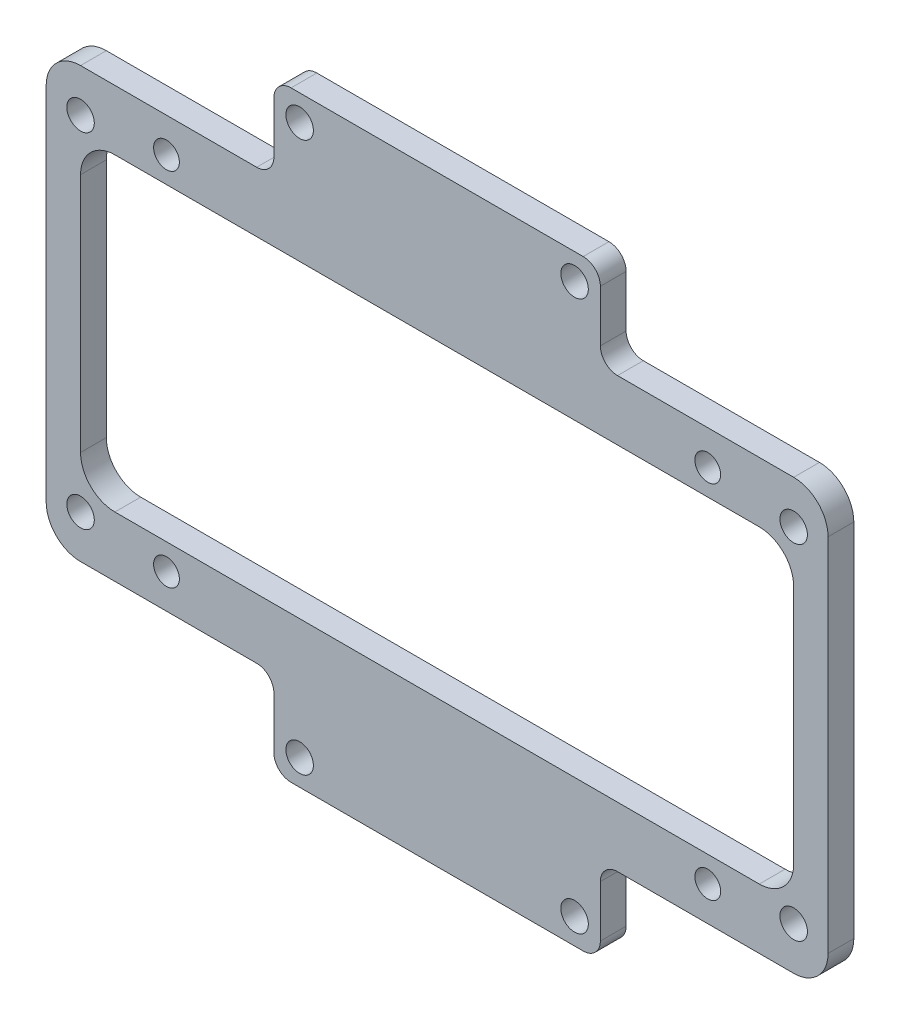
SolidWorks part; units mm, degrees
material "A-玻璃纤维"
ref_plane "前视基准面" through (0, 0, 0) normal (0, 0, 1) x (1, 0, 0)
ref_plane "上视基准面" through (0, 0, 0) normal (0, 1, 0) x (1, 0, 0)
ref_plane "右视基准面" through (0, 0, 0) normal (1, 0, 0) x (0, 0, -1)
sketch "草图1" plane through (0, 0, 0) normal (0, 0, 1) x (1, 0, 0)
  line L1 (-45.5, -25) -> (45.5, -25)
  line L2 (-45.5, -25) -> (-45.5, 25)
  line L3 (-45.5, 25) -> (45.5, 25)
  line L4 (45.5, -25) -> (45.5, 25)
  line L5 (-45.5, -25) -> (45.5, 25) construction
  line L6 (-45.5, 25) -> (45.5, -25) construction
  line L7 (-41.5, -18) -> (41.5, -18)
  line L8 (-41.5, -18) -> (-41.5, 18)
  line L9 (-41.5, 18) -> (41.5, 18)
  line L10 (41.5, -18) -> (41.5, 18)
  line L11 (-41.5, -18) -> (41.5, 18) construction
  line L12 (-41.5, 18) -> (41.5, -18) construction
  point P0 (0, 0)
  point P6 (0, 0)
  dimension "D1" = 50
  dimension "D2" = 91
  dimension "D3" = 36
  dimension "D4" = 83
extrude "凸台-拉伸1" add sketch "草图1" along normal blind 3
sketch "草图2" plane through (0, 0, 3) normal (0, 0, 1) x (1, 0, 0)
  line L1 (-31.5, -21) -> (31.5, -21) construction
  line L2 (-31.5, -21) -> (-31.5, 21) construction
  line L3 (-31.5, 21) -> (31.5, 21) construction
  line L4 (31.5, -21) -> (31.5, 21) construction
  line L5 (-31.5, -21) -> (31.5, 21) construction
  line L6 (-31.5, 21) -> (31.5, -21) construction
  circle A0 centre (31.5, 21) radius 1.5
  circle A1 centre (31.5, -21) radius 1.5
  circle A2 centre (-31.5, -21) radius 1.5
  circle A3 centre (-31.5, 21) radius 1.5
  point P0 (0, 0)
  dimension "D3" = 3
  dimension "D1" = 42
  dimension "D2" = 63
extrude "切除-拉伸1" cut sketch "草图2" against normal blind 3
sketch "草图3" plane through (0, 0, 3) normal (0, 0, 1) x (1, 0, 0)
  line L1 (-41.5, -20) -> (41.5, -20) construction
  line L2 (-41.5, -20) -> (-41.5, 20) construction
  line L3 (-41.5, 20) -> (41.5, 20) construction
  line L4 (41.5, -20) -> (41.5, 20) construction
  line L5 (-41.5, -20) -> (41.5, 20) construction
  line L6 (-41.5, 20) -> (41.5, -20) construction
  circle A0 centre (41.5, 20) radius 1.6
  circle A1 centre (41.5, -20) radius 1.6
  circle A2 centre (-41.5, -20) radius 1.6
  circle A3 centre (-41.5, 20) radius 1.6
  point P0 (0, 0)
  dimension "D3" = 3.2
  dimension "D1" = 83
  dimension "D2" = 40
extrude "切除-拉伸2" cut sketch "草图3" against normal blind 3
fillet "圆角1" radius 4 8 edges at (-41.5, -18, 1.5) (41.5, -18, 1.5) (45.5, -25, 1.5) (-45.5, -25, 1.5) (-45.5, 25, 1.5) (45.5, 25, 1.5) (41.5, 18, 1.5) (-41.5, 18, 1.5)
sketch "草图4" plane through (0, 0, 0) normal (0, 0, -1) x (-1, 0, 0)
  line L0 (-45.5, -21) -> (-45.5, 21) construction
  line L1 (-45.5, 17.5) -> (-75.5, 17.5)
  line L2 (-45.5, 17.5) -> (-45.5, -17.5)
  line L3 (-45.5, -17.5) -> (-75.5, -17.5)
  line L4 (-75.5, 17.5) -> (-75.5, -17.5)
  line L5 (-45.5, 0) -> (0, 0) construction
  dimension "D1" = 35
  dimension "D2" = 30
extrude "凸台-拉伸2" add sketch "草图4" against normal up to surface (3 mm away) up to face at (-39.9, 20, 3)
sketch "草图5" plane through (0, 0, 0) normal (0, 0, -1) x (-1, 0, 0)
  line L0 (-70.5, 17.5) -> (-70.5, -17.5) construction
  line L3 (-70.5, 0) -> (0, 0) construction
  line L4 (-75.5, 17.5) -> (-75.5, -17.5) construction
  circle A0 centre (-70.5, -12) radius 1.25
  circle A1 centre (-70.5, 12) radius 1.25
  dimension "D2" = 2.5
  dimension "D1" = 12
  dimension "D3" = 5
extrude "切除-拉伸3" cut sketch "草图5" against normal blind 10
fillet "圆角2" radius 3 4 edges at (45.5, 17.5, 1.5) (75.5, 17.5, 1.5) (75.5, -17.5, 1.5) (45.5, -17.5, 1.5)
sketch "草图6" plane through (0, 0, 0) normal (0, 0, -1) x (-1, 0, 0)
  line L0 (-48.5, 17.5) -> (-72.5, 17.5) construction
  line L5 (-66.5, 13.5) -> (-48.5, 13.5)
  line L6 (-66.5, 13.5) -> (-66.5, -13.5)
  line L7 (-66.5, -13.5) -> (-48.5, -13.5)
  line L8 (-48.5, 13.5) -> (-48.5, -13.5)
  line L9 (-72.5, -17.5) -> (-48.5, -17.5) construction
  circle A0 centre (-70.5, -12) radius 1.25 construction
  dimension "D1" = 4
  dimension "D2" = 4
  dimension "D3" = 4
  dimension "D4" = 3
extrude "切除-拉伸4" cut sketch "草图6" against normal blind 10
fillet "圆角3" radius 2 4 edges at (48.5, 13.5, 1.5) (48.5, -13.5, 1.5) (66.5, -13.5, 1.5) (66.5, 13.5, 1.5)
sketch "草图7" plane through (0, 0, 0) normal (0, 0, -1) x (-1, 0, 0)
  line L0 (-19, 25) -> (19, 25)
  line L1 (-16, -32) -> (16, -32) construction
  line L2 (-16, -32) -> (-16, 32) construction
  line L3 (-16, 32) -> (16, 32) construction
  line L4 (16, -32) -> (16, 32) construction
  line L5 (0, 32) -> (0, -32) construction
  line L6 (-16, 0) -> (16, 0) construction
  line L7 (-19, -35) -> (19, -35)
  line L8 (-19, -35) -> (-19, -25)
  line L9 (-19, 35) -> (19, 35)
  line L10 (19, -35) -> (19, -25)
  line L11 (0, 35) -> (0, -35) construction
  line L12 (-19, 0) -> (19, 0) construction
  line L13 (-41.5, 25) -> (41.5, 25) construction
  line L14 (-19, -25) -> (19, -25)
  line L15 (41.5, -25) -> (-41.5, -25) construction
  line L16 (19, 25) -> (19, 35)
  line L17 (-19, 25) -> (-19, 35)
  circle A0 centre (16, -32) radius 1.6
  circle A1 centre (-16, -32) radius 1.6
  circle A2 centre (-16, 32) radius 1.6
  circle A3 centre (16, 32) radius 1.6
  point P0 (0, 0)
  point P4 (0, 0)
  dimension "D6" = 3.2
  dimension "D1" = 64
  dimension "D2" = 32
  dimension "D3" = 38
  dimension "D4" = 3
  dimension "D5" = 3
extrude "凸台-拉伸3" add sketch "草图7" against normal up to surface (3 mm away) up to face at (57.5, 0, 3)
fillet "圆角4" radius 2 4 edges at (-19, -35, 1.5) (19, -35, 1.5) (-19, 35, 1.5) (19, 35, 1.5)
fillet "圆角5" radius 2 4 edges at (-19, -25, 1.5) (19, -25, 1.5) (19, 25, 1.5) (-19, 25, 1.5)
sketch "草图8" plane through (0, 0, 3) normal (0, 0, 1) x (1, 0, 0)
  line L0 (75.5, -14.5) -> (75.5, 14.5) construction
  line L1 (45.5, -20.5) -> (75.5, -20.5)
  line L2 (45.5, -20.5) -> (45.5, 20.5)
  line L3 (45.5, 20.5) -> (75.5, 20.5)
  line L4 (75.5, -20.5) -> (75.5, 20.5)
  point P7 (45.5, 0)
extrude "切除-拉伸5" cut sketch "草图8" against normal blind 10
